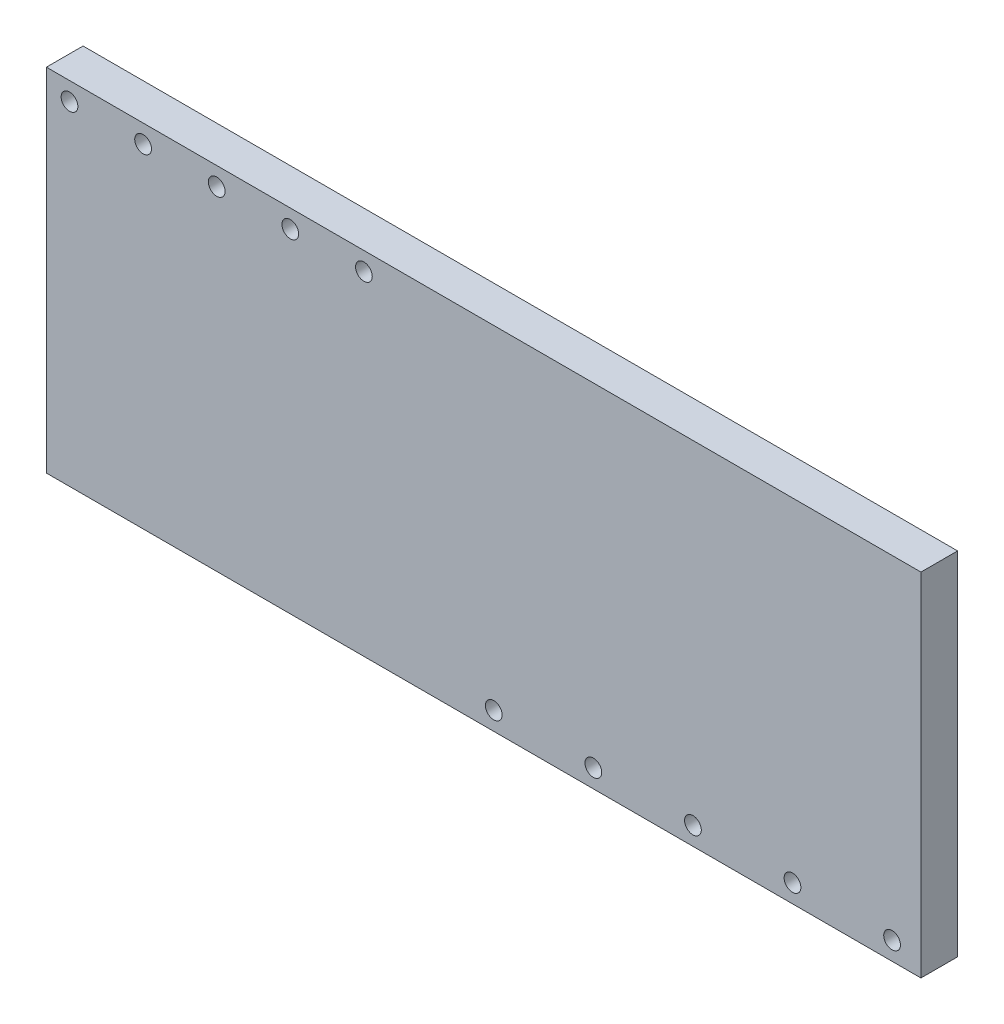
SolidWorks part; units mm, degrees
material "6061 Alloy"
ref_plane "Front Plane" through (0, 0, 0) normal (0, 0, 1) x (1, 0, 0)
ref_plane "Top Plane" through (0, 0, 0) normal (0, 1, 0) x (1, 0, 0)
ref_plane "Right Plane" through (0, 0, 0) normal (1, 0, 0) x (0, 0, -1)
sketch "Sketch1" plane through (0, 0, 0) normal (0, 0, 1) x (1, 0, 0)
  line L1 (-75.75, 30.45) -> (75.75, 30.45)
  line L2 (-75.75, 30.45) -> (-75.75, -30.45)
  line L3 (-75.75, -30.45) -> (75.75, -30.45)
  line L4 (75.75, 30.45) -> (75.75, -30.45)
  line L5 (-75.75, 30.45) -> (75.75, -30.45) construction
  line L6 (-75.75, -30.45) -> (75.75, 30.45) construction
  point P0 (0, 0)
  dimension "D1" = 151.5
  dimension "D2" = 60.9
extrude "Boss-Extrude1" add sketch "Sketch1" along normal blind 6.35
sketch "Sketch2" plane through (0, 0, 6.35) normal (0, 0, 1) x (1, 0, 0)
  line L8 (-3.25, -30.45) -> (75.75, -30.45)
  line L9 (75.75, -30.45) -> (75.75, -24.1)
  line L10 (75.75, -24.1) -> (-3.25, -24.1)
  line L11 (-3.25, -24.1) -> (-3.25, -30.45)
  line L12 (-16.75, 30.45) -> (-75.75, 30.45)
  line L13 (-75.75, 30.45) -> (-75.75, 24.1)
  line L14 (-75.75, 24.1) -> (-16.75, 24.1)
  line L15 (-16.75, 24.1) -> (-16.75, 30.45)
  circle A2 centre (1.75, -27.275) radius 1.025
  circle A4 centre (19, -27.275) radius 1.025
  circle A6 centre (70.75, -27.275) radius 1.025
  circle A8 centre (53.5, -27.275) radius 1.025
  circle A10 centre (36.25, -27.275) radius 1.025
  circle A12 centre (-20.75, 27.275) radius 1.025
  circle A14 centre (-33.5, 27.275) radius 1.025
  circle A16 centre (-71.75, 27.275) radius 1.025
  circle A18 centre (-59, 27.275) radius 1.025
  circle A20 centre (-46.25, 27.275) radius 1.025
hole_wizard "M2.5 Clearance Hole1" positions "Sketch3" profile "Sketch4" hole size "M2.5" standard "ANSI Metric" end condition through all
sketch "Sketch3" plane through (0, 0, 6.35) normal (0, 0, 1) x (1, 0, 0)
  point P0 (-71.75, 27.275)
  point P3 (-59, 27.275)
  point P6 (-46.25, 27.275)
  point P15 (-33.5, 27.275)
  point P18 (-20.75, 27.275)
  point P21 (1.75, -27.275)
  point P24 (19, -27.275)
  point P27 (36.25, -27.275)
  point P30 (53.5, -27.275)
  point P33 (70.75, -27.275)
sketch "Sketch4" plane through (-71.75, 27.275, 6.35) normal (1, 0, 0) x (0, -1, 0)
  line L0 (0, 0) -> (0, 6.35)
  line L1 (0, 6.35) -> (1.45, 6.35)
  line L2 (1.45, 6.35) -> (1.45, 0)
  line L5 (1.45, 0) -> (0, 0)
  line L11 (0, -6.35) -> (0, 107.95) construction
  dimension "Thru Hole Dia." = 2.9
  dimension "Thru Hole Depth" = 6.35
